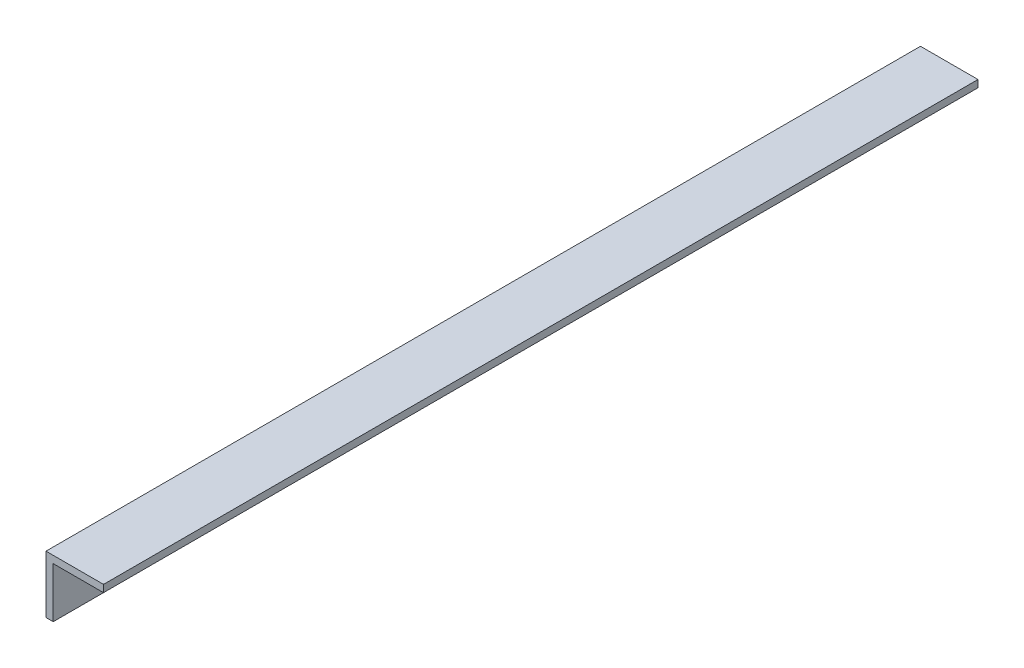
SolidWorks part; units mm, degrees
ref_plane "Front Plane" through (0, 0, 0) normal (0, 0, 1) x (1, 0, 0)
ref_plane "Top Plane" through (0, 0, 0) normal (0, 1, 0) x (1, 0, 0)
ref_plane "Right Plane" through (0, 0, 0) normal (1, 0, 0) x (0, 0, -1)
sketch "Sketch1" plane through (0, 0, 0) normal (0, 0, 1) x (1, 0, 0)
  line L0 (0, 0) -> (0, 25.4)
  line L1 (0, 25.4) -> (25.4, 25.4)
  line L2 (25.4, 25.4) -> (25.4, 22.225)
  line L3 (25.4, 22.225) -> (3.175, 22.225)
  line L4 (3.175, 22.225) -> (3.175, 0)
  line L5 (3.175, 0) -> (0, 0)
  dimension "D1" = 25.4
  dimension "D2" = 25.4
  dimension "D3" = 3.175
  dimension "D4" = 3.175
extrude "Boss-Extrude1" add sketch "Sketch1" along normal blind 386.08
sketch "Sketch2" plane through (3.175, 0, 0) normal (1, 0, 0) x (0, 0, -1)
  line L0 (0, 0) -> (0, 22.225) construction
  line L1 (-386.08, 25.4) -> (0, 25.4) construction
  circle A0 centre (-19.05, 12.7) radius 3.9688
  circle A1 centre (-158.75, 12.7) radius 3.9687
  point P4 (0, 11.1125)
  dimension "D1" = 19.05
  dimension "D3" = 7.9375
  dimension "D2" = 139.7
  dimension "D4" = 12.7
  dimension "D5" = 12.7
extrude "Cut-Extrude1" cut sketch "Sketch2" against normal blind 6.35
